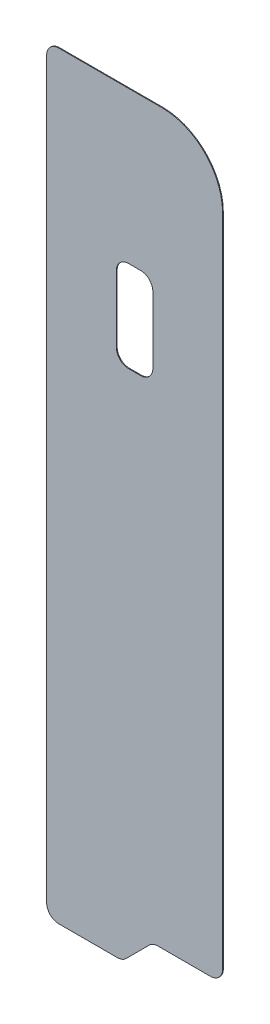
SolidWorks part; units mm, degrees
material "Melinex 454"
ref_plane "Front Plane" through (0, 0, 0) normal (0, 0, 1) x (1, 0, 0)
ref_plane "Top Plane" through (0, 0, 0) normal (0, 1, 0) x (1, 0, 0)
ref_plane "Right Plane" through (0, 0, 0) normal (1, 0, 0) x (0, 0, -1)
sketch "Sketch9" plane through (0, 0, 0) normal (0, 0, 1) x (1, 0, 0)
  line L0 (0, 60) -> (0, -60) construction
  line L1 (-12.5, 60) -> (4.5, 60)
  line L2 (-14.5, 58) -> (-14.5, -58)
  line L3 (-12.5, -60) -> (12.5, -60)
  line L4 (14.5, 50) -> (14.5, -58)
  line L5 (-14.5, 60) -> (14.5, -60) construction
  line L6 (-14.5, -60) -> (14.5, 60) construction
  line L7 (-14.5, 0) -> (14.5, 0) construction
  line L8 (0, -55) -> (0, 55) construction
  arc A0 (-14.5, -58) -> (-12.5, -60) centre (-12.5, -58) ccw
  arc A1 (12.5, -60) -> (14.5, -58) centre (12.5, -58) ccw
  arc A2 (4.5, 60) -> (14.5, 50) centre (4.5, 50) cw
  arc A3 (-12.5, 60) -> (-14.5, 58) centre (-12.5, 58) ccw
  point P0 (0, 0)
extrude "Boss-Extrude6" add sketch "Sketch9" along normal blind 0.125
sketch "Sketch10" plane through (0, 0, 0) normal (0, 0, -1) x (-1, 0, 0)
  line L0 (14.5, -58) -> (14.5, -63)
  line L1 (12.5, -65) -> (2.8284, -65)
  line L2 (1.4142, -64.4142) -> (-2.4142, -60.5858)
  line L3 (12.5, -60) -> (-12.5, -60) construction
  line L6 (0.5, -62.5) -> (-0.5, -62.5) construction
  line L8 (-3.8284, -60) -> (-12.5, -60)
  line L9 (-12.5, -60) -> (-12.5, -58)
  line L10 (-12.5, -58) -> (14.5, -58)
  line L11 (0, -62.5) -> (0, -60) construction
  line L12 (2.4142, -60.5858) -> (-1.4142, -64.4142) construction
  line L13 (-2.8284, -65) -> (-12.5, -65) construction
  arc A3 (-2.4142, -60.5858) -> (-3.8284, -60) centre (-3.8284, -62) ccw
  arc A4 (2.8284, -65) -> (1.4142, -64.4142) centre (2.8284, -63) cw
  arc A5 (14.5, -63) -> (12.5, -65) centre (12.5, -63) cw
  point P22 (-3, -60)
  point P28 (0, -62.5)
  dimension "D1" = 2
extrude "Boss-Extrude7" add sketch "Sketch10" against normal up to surface (0.125 mm away) up to face at (-0.7929, -0.7929, 0.125)
sketch "Sketch11" plane through (0, 0, 0.125) normal (0, 0, 1) x (1, 0, 0)
  line L22 (-1, 20) -> (1, 20)
  line L23 (3, 22) -> (3, 33)
  line L24 (1, 35) -> (-1, 35)
  line L25 (-3, 33) -> (-3, 22)
  arc A27 (1, 20) -> (3, 22) centre (1, 22) ccw
  arc A28 (-3, 22) -> (-1, 20) centre (-1, 22) ccw
  arc A29 (3, 33) -> (1, 35) centre (1, 33) ccw
  arc A30 (-1, 35) -> (-3, 33) centre (-1, 33) ccw
extrude "Cut-Extrude2" cut sketch "Sketch11" against normal through all
